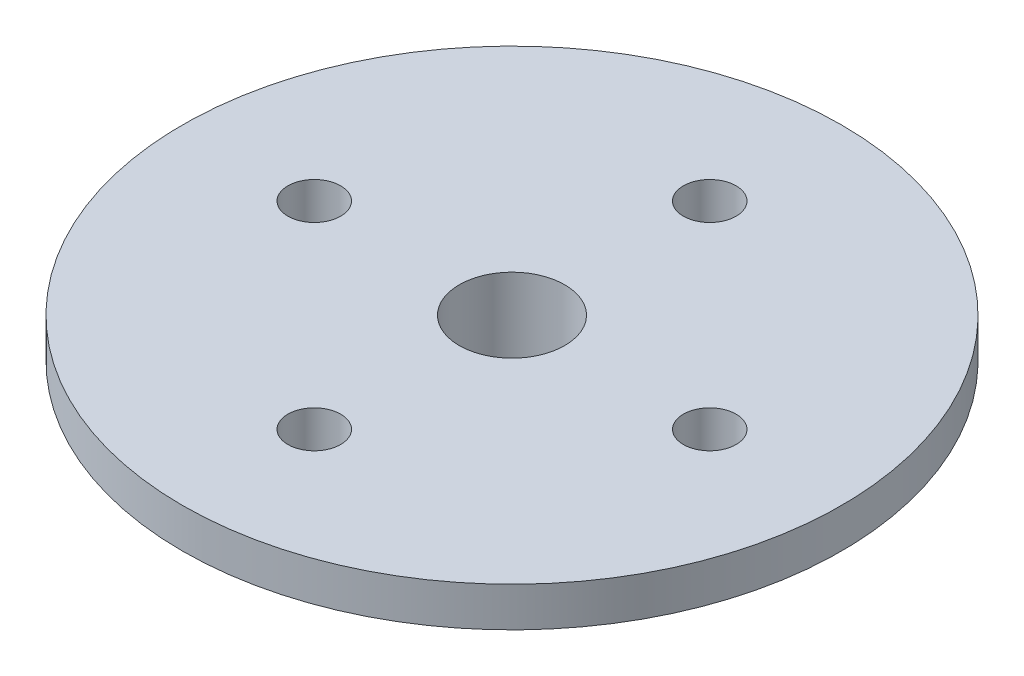
SolidWorks part; units mm, degrees
ref_plane "Front" through (0, 0, 0) normal (0, 0, 1) x (1, 0, 0)
ref_plane "Top" through (0, 0, 0) normal (0, 1, 0) x (1, 0, 0)
ref_plane "Right" through (0, 0, 0) normal (1, 0, 0) x (0, 0, -1)
sketch "草图1" plane through (0, 0, 0) normal (0, 0, 1) x (1, 0, 0)
  line L0 (0, 11.2953) -> (0, -12.9964) construction
  line L1 (0, 3) -> (-25, 3)
  line L2 (-25, 3) -> (-25, 0)
  line L3 (-25, 0) -> (-18.5, 0)
  line L4 (-18.5, 0) -> (-18.5, -3)
  line L5 (-18.5, -3) -> (0, -3)
  line L6 (0, 3) -> (0, -3)
  dimension "D1" = 25
  dimension "D2" = 18.5
  dimension "D3" = 3
  dimension "D4" = 3
revolve "旋转1" add sketch "草图1" angle 360 about L0
sketch "草图2" plane through (0, 3, 0) normal (0, 1, 0) x (1, 0, 0)
  line L0 (0, 26.6501) -> (0, -27.2111) construction
  circle A0 centre (0, 15) radius 2
  circle A1 centre (15, 0) radius 2
  circle A2 centre (0, -15) radius 2
  circle A3 centre (-15, 0) radius 2
  circle A4 centre (0, 0) radius 4
  point P14 (0, 0)
  dimension "D1" = 4
  dimension "D2" = 4
  dimension "D3" = 8
  dimension "D4" = 15
extrude "切除-拉伸1" cut sketch "草图2" against normal through all
